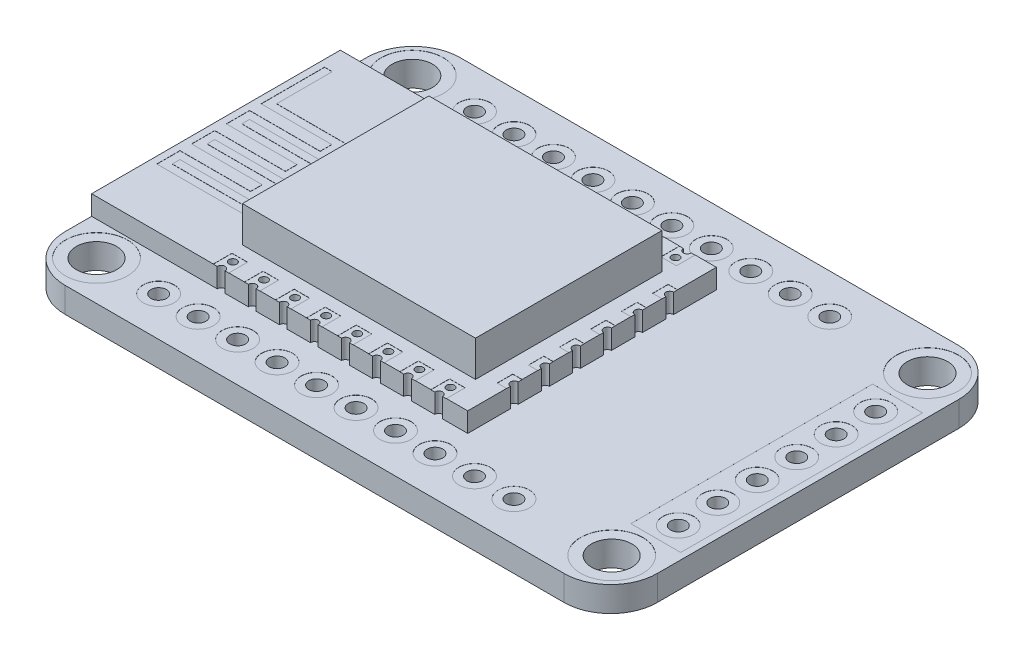
SolidWorks part; units mm, degrees
ref_plane "Front Plane" through (0, 0, 0) normal (0, 0, 1) x (1, 0, 0)
ref_plane "Top Plane" through (0, 0, 0) normal (0, 1, 0) x (1, 0, 0)
ref_plane "Right Plane" through (0, 0, 0) normal (1, 0, 0) x (0, 0, -1)
sketch "Sketch1" plane through (0, 0, 0) normal (0, 1, 0) x (1, 0, 0)
  line L1 (-19.05, -12.7) -> (19.05, -12.7)
  line L2 (-19.05, -12.7) -> (-19.05, 12.7)
  line L3 (-19.05, 12.7) -> (19.05, 12.7)
  line L4 (19.05, -12.7) -> (19.05, 12.7)
  line L5 (-19.05, -12.7) -> (19.05, 12.7) construction
  line L6 (-19.05, 12.7) -> (19.05, -12.7) construction
  point P0 (0, 0)
  dimension "D1" = 25.4
  dimension "D2" = 38.1
extrude "Boss-Extrude1" add sketch "Sketch1" along normal blind 1.62
fillet "Fillet1" radius 3 4 edges at (-19.05, 0.81, -12.7) (19.05, 0.81, -12.7) (19.05, 0.81, 12.7) (-19.05, 0.81, 12.7)
sketch "Sketch2" plane through (0, 1.62, 0) normal (0, 1, 0) x (1, 0, 0)
  line L0 (-20.6005, 0) -> (20.6768, 0) construction
  line L1 (0, 14.1473) -> (0, -15.4074) construction
  circle A0 centre (-16.575, 10.16) radius 1.3
  circle A1 centre (16.575, 10.16) radius 1.3
  circle A2 centre (16.575, -10.16) radius 1.3
  circle A3 centre (-16.575, -10.16) radius 1.3
  dimension "D1" = 2.6
  dimension "D2" = 10.16
  dimension "D3" = 16.575
extrude "Cut-Extrude1" cut sketch "Sketch2" against normal through all
sketch "Sketch4" plane through (0, 1.62, 0) normal (0, 1, 0) x (1, 0, 0)
  line L0 (-20.7466, 0) -> (20.5407, 0) construction
  line L1 (0, 13.8309) -> (0, -14.5222) construction
  circle A0 centre (16.575, 10.16) radius 2
  circle A1 centre (-16.575, 10.16) radius 2
  circle A2 centre (16.575, -10.16) radius 2
  circle A3 centre (-16.575, -10.16) radius 2
  dimension "D1" = 4
extrude "Cut-Extrude2" cut sketch "Sketch4" against normal blind 0.01
sketch "Sketch3" plane through (0, 1.62, 0) normal (0, 1, 0) x (1, 0, 0)
  line L0 (-21.1351, 0) -> (21.8987, 0) construction
  line L1 (16.575, 10.16) -> (-16.575, 10.16) construction
  line L2 (19.05, -9.7) -> (19.05, 9.7) construction
  line L3 (17.05, 6.35) -> (17.05, -6.35) construction
  circle A0 centre (-12.575, 10.16) radius 0.5
  circle A1 centre (-10.035, 10.16) radius 0.5
  circle A2 centre (-7.495, 10.16) radius 0.5
  circle A3 centre (-4.955, 10.16) radius 0.5
  circle A4 centre (-2.415, 10.16) radius 0.5
  circle A5 centre (0.125, 10.16) radius 0.5
  circle A6 centre (2.665, 10.16) radius 0.5
  circle A7 centre (5.205, 10.16) radius 0.5
  circle A8 centre (7.745, 10.16) radius 0.5
  circle A9 centre (10.285, 10.16) radius 0.5
  circle A10 centre (-16.575, 10.16) radius 1.3 construction
  circle A13 centre (10.285, -10.16) radius 0.5
  circle A14 centre (7.745, -10.16) radius 0.5
  circle A15 centre (5.205, -10.16) radius 0.5
  circle A16 centre (2.665, -10.16) radius 0.5
  circle A17 centre (0.125, -10.16) radius 0.5
  circle A18 centre (-2.415, -10.16) radius 0.5
  circle A19 centre (-4.955, -10.16) radius 0.5
  circle A20 centre (-7.495, -10.16) radius 0.5
  circle A21 centre (-10.035, -10.16) radius 0.5
  circle A22 centre (-12.575, -10.16) radius 0.5
  circle A23 centre (17.05, 6.35) radius 0.5
  circle A24 centre (17.05, 3.81) radius 0.5
  circle A25 centre (17.05, 1.27) radius 0.5
  circle A26 centre (17.05, -1.27) radius 0.5
  circle A27 centre (17.05, -3.81) radius 0.5
  circle A28 centre (17.05, -6.35) radius 0.5
  point P53 (17.05, 0)
  dimension "D1" = 1
  dimension "D5" = 2
  dimension "D3" = 2.54
  dimension "D4" = 4
  dimension "D7" = 2.54
  dimension "D2" = 10
  dimension "D6" = 6
extrude "Cut-Extrude3" cut sketch "Sketch3" against normal through all
sketch "Sketch6" plane through (0, 1.62, 0) normal (0, 1, 0) x (1, 0, 0)
  circle A0 centre (2.665, 10.16) radius 1
  circle A1 centre (2.665, 10.16) radius 0.5
  circle A2 centre (2.665, 10.16) radius 0.5 construction
  circle A3 centre (0.125, 10.16) radius 0.5
  circle A4 centre (0.125, 10.16) radius 0.5 construction
  circle A5 centre (-2.415, 10.16) radius 0.5
  circle A6 centre (-2.415, 10.16) radius 0.5 construction
  circle A7 centre (-4.955, 10.16) radius 0.5
  circle A8 centre (-4.955, 10.16) radius 0.5 construction
  circle A9 centre (-7.495, 10.16) radius 0.5
  circle A10 centre (-7.495, 10.16) radius 0.5 construction
  circle A11 centre (-10.035, 10.16) radius 0.5
  circle A12 centre (-10.035, 10.16) radius 0.5 construction
  circle A13 centre (-12.575, 10.16) radius 0.5
  circle A14 centre (-12.575, 10.16) radius 0.5 construction
  circle A15 centre (5.205, -10.16) radius 0.5
  circle A16 centre (5.205, -10.16) radius 0.5 construction
  circle A17 centre (7.745, -10.16) radius 0.5
  circle A18 centre (7.745, -10.16) radius 0.5 construction
  circle A19 centre (10.285, -10.16) radius 0.5
  circle A20 centre (10.285, -10.16) radius 0.5 construction
  circle A21 centre (10.285, 10.16) radius 0.5
  circle A22 centre (10.285, 10.16) radius 0.5 construction
  circle A23 centre (7.745, 10.16) radius 0.5
  circle A24 centre (7.745, 10.16) radius 0.5 construction
  circle A25 centre (5.205, 10.16) radius 0.5
  circle A26 centre (5.205, 10.16) radius 0.5 construction
  circle A27 centre (-12.575, -10.16) radius 0.5
  circle A28 centre (-12.575, -10.16) radius 0.5 construction
  circle A29 centre (-10.035, -10.16) radius 0.5
  circle A30 centre (-10.035, -10.16) radius 0.5 construction
  circle A31 centre (-7.495, -10.16) radius 0.5
  circle A32 centre (-7.495, -10.16) radius 0.5 construction
  circle A33 centre (-4.955, -10.16) radius 0.5
  circle A34 centre (-4.955, -10.16) radius 0.5 construction
  circle A35 centre (-2.415, -10.16) radius 0.5
  circle A36 centre (-2.415, -10.16) radius 0.5 construction
  circle A37 centre (0.125, -10.16) radius 0.5
  circle A38 centre (0.125, -10.16) radius 0.5 construction
  circle A39 centre (2.665, -10.16) radius 0.5
  circle A40 centre (2.665, -10.16) radius 0.5 construction
  circle A41 centre (17.05, -3.81) radius 0.5
  circle A42 centre (17.05, -3.81) radius 0.5 construction
  circle A43 centre (17.05, -1.27) radius 0.5
  circle A44 centre (17.05, -1.27) radius 0.5 construction
  circle A45 centre (17.05, 1.27) radius 0.5
  circle A46 centre (17.05, 1.27) radius 0.5 construction
  circle A47 centre (17.05, 3.81) radius 0.5
  circle A48 centre (17.05, 3.81) radius 0.5 construction
  circle A49 centre (17.05, 6.35) radius 0.5
  circle A50 centre (17.05, 6.35) radius 0.5 construction
  circle A51 centre (17.05, -6.35) radius 0.5
  circle A52 centre (17.05, -6.35) radius 0.5 construction
  circle A53 centre (0.125, 10.16) radius 1
  circle A54 centre (-2.415, 10.16) radius 1
  circle A55 centre (-4.955, 10.16) radius 1
  circle A56 centre (-7.495, 10.16) radius 1
  circle A57 centre (-10.035, 10.16) radius 1
  circle A58 centre (-12.575, 10.16) radius 1
  circle A59 centre (5.205, -10.16) radius 1
  circle A60 centre (7.745, -10.16) radius 1
  circle A61 centre (10.285, -10.16) radius 1
  circle A62 centre (10.285, 10.16) radius 1
  circle A63 centre (7.745, 10.16) radius 1
  circle A64 centre (5.205, 10.16) radius 1
  circle A65 centre (-12.575, -10.16) radius 1
  circle A66 centre (-10.035, -10.16) radius 1
  circle A67 centre (-7.495, -10.16) radius 1
  circle A68 centre (-4.955, -10.16) radius 1
  circle A69 centre (-2.415, -10.16) radius 1
  circle A70 centre (0.125, -10.16) radius 1
  circle A71 centre (2.665, -10.16) radius 1
  circle A72 centre (17.05, -3.81) radius 1
  circle A73 centre (17.05, -1.27) radius 1
  circle A74 centre (17.05, 1.27) radius 1
  circle A75 centre (17.05, 3.81) radius 1
  circle A76 centre (17.05, 6.35) radius 1
  circle A77 centre (17.05, -6.35) radius 1
  dimension "D1" = 0
  dimension "D2" = 0
  dimension "D3" = 0
  dimension "D4" = 0
  dimension "D5" = 0
  dimension "D6" = 0
  dimension "D7" = 0
  dimension "D8" = 0
  dimension "D9" = 0
  dimension "D10" = 0
  dimension "D11" = 0
  dimension "D12" = 0
  dimension "D13" = 0
  dimension "D14" = 0
  dimension "D15" = 0
  dimension "D16" = 0
  dimension "D17" = 0
  dimension "D18" = 0
  dimension "D19" = 0
  dimension "D20" = 0
  dimension "D21" = 0
  dimension "D22" = 0
  dimension "D23" = 0
  dimension "D24" = 0
  dimension "D25" = 0
  dimension "D26" = 0
  dimension "D27" = 0.5
extrude "Cut-Extrude4" cut sketch "Sketch6" against normal blind 0.01
sketch "Sketch7" plane through (0, 1.62, 0) normal (0, 1, 0) x (1, 0, 0)
  line L0 (-19.05, 9.7) -> (-19.05, -9.7) construction
  line L1 (-19.05, 8) -> (5.15, 8)
  line L2 (-19.05, 8) -> (-19.05, -8)
  line L3 (-19.05, -8) -> (5.15, -8)
  line L4 (5.15, 8) -> (5.15, -8)
  point P6 (-19.05, 0)
  dimension "D1" = 16
  dimension "D2" = 24.2
extrude "Boss-Extrude2" add sketch "Sketch7" along normal blind 1.26
sketch "Sketch8" plane through (0, 2.88, 0) normal (0, 1, 0) x (1, 0, 0)
  line L0 (-19.05, 8) -> (-19.05, -8) construction
  line L1 (-11.35, 6) -> (3.65, 6)
  line L2 (-11.35, 6) -> (-11.35, -6)
  line L3 (-11.35, -6) -> (3.65, -6)
  line L4 (3.65, 6) -> (3.65, -6)
  point P4 (-11.35, 0)
  dimension "D1" = 15
  dimension "D2" = 12
  dimension "D3" = 7.7
extrude "Boss-Extrude3" add sketch "Sketch8" along normal blind 2.3
sketch "Sketch9" plane through (0, 2.88, 0) normal (0, 1, 0) x (1, 0, 0)
  line L0 (-21.5126, 0) -> (22.1016, 0) construction
  line L1 (-19.05, 8) -> (-19.05, -8) construction
  line L2 (5.15, 8) -> (-19.05, 8) construction
  line L3 (5.15, -8) -> (5.15, 8) construction
  line L4 (5.15, 5) -> (5.15, -5) construction
  circle A0 centre (-10.7186, 7.2412) radius 0.25
  circle A1 centre (-8.7186, 7.2412) radius 0.25
  circle A2 centre (-6.7186, 7.2412) radius 0.25
  circle A3 centre (-4.7186, 7.2412) radius 0.25
  circle A4 centre (-2.7186, 7.2412) radius 0.25
  circle A5 centre (-0.7186, 7.2412) radius 0.25
  circle A6 centre (1.2814, 7.2412) radius 0.25
  circle A7 centre (3.2814, 7.2412) radius 0.25
  circle A8 centre (-8.7186, 7.9912) radius 0.25
  circle A9 centre (-6.7186, 7.9912) radius 0.25
  circle A10 centre (-4.7186, 7.9912) radius 0.25
  circle A11 centre (-2.7186, 7.9912) radius 0.25
  circle A12 centre (-0.7186, 7.9912) radius 0.25
  circle A13 centre (1.2814, 7.9912) radius 0.25
  circle A14 centre (3.2814, 7.9912) radius 0.25
  circle A15 centre (-10.7186, 7.9912) radius 0.25
  circle A16 centre (-10.7186, -7.9912) radius 0.25
  circle A17 centre (3.2814, -7.9912) radius 0.25
  circle A18 centre (1.2814, -7.9912) radius 0.25
  circle A19 centre (-0.7186, -7.9912) radius 0.25
  circle A20 centre (-2.7186, -7.9912) radius 0.25
  circle A21 centre (-4.7186, -7.9912) radius 0.25
  circle A22 centre (-6.7186, -7.9912) radius 0.25
  circle A23 centre (-8.7186, -7.9912) radius 0.25
  circle A24 centre (3.2814, -7.2412) radius 0.25
  circle A25 centre (1.2814, -7.2412) radius 0.25
  circle A26 centre (-0.7186, -7.2412) radius 0.25
  circle A27 centre (-2.7186, -7.2412) radius 0.25
  circle A28 centre (-4.7186, -7.2412) radius 0.25
  circle A29 centre (-6.7186, -7.2412) radius 0.25
  circle A30 centre (-8.7186, -7.2412) radius 0.25
  circle A31 centre (-10.7186, -7.2412) radius 0.25
  circle A32 centre (5.15, 5) radius 0.25
  circle A33 centre (5.15, 3) radius 0.25
  circle A34 centre (5.15, 1) radius 0.25
  circle A35 centre (5.15, -1) radius 0.25
  circle A36 centre (5.15, -3) radius 0.25
  circle A37 centre (5.15, -5) radius 0.25
  point P75 (5.15, 0)
  dimension "D1" = 0.5
  dimension "D8" = 0.5
  dimension "D4" = 0.75
  dimension "D5" = 2
  dimension "D6" = 8.3314
  dimension "D7" = 0.7588
  dimension "D10" = 2
  dimension "D2" = 8
  dimension "D3" = 2
  dimension "D9" = 6
extrude "Cut-Extrude5" cut sketch "Sketch9" against normal up to surface (1.26 mm away) up to face at (16.575, 1.62, -8.16)
sketch "Sketch10" plane through (0, 2.88, 0) normal (0, 1, 0) x (1, 0, 0)
  line L0 (-10.9685, 8) -> (-19.05, 8) construction
  line L1 (-11.2186, 8) -> (-10.2186, 8)
  line L2 (-11.2186, 8) -> (-11.2186, 6.8)
  line L3 (-11.2186, 6.8) -> (-10.2186, 6.8)
  line L4 (-10.2186, 8) -> (-10.2186, 6.8)
  line L5 (-19.6707, 0) -> (20.0452, 0) construction
  line L6 (-9.2186, 8) -> (-8.2186, 8)
  line L7 (-9.2186, 8) -> (-9.2186, 6.8)
  line L8 (-9.2186, 6.8) -> (-8.2186, 6.8)
  line L9 (-8.2186, 8) -> (-8.2186, 6.8)
  line L10 (-7.2186, 8) -> (-6.2186, 8)
  line L11 (-7.2186, 8) -> (-7.2186, 6.8)
  line L12 (-7.2186, 6.8) -> (-6.2186, 6.8)
  line L13 (-6.2186, 8) -> (-6.2186, 6.8)
  line L14 (-5.2186, 8) -> (-4.2186, 8)
  line L15 (-5.2186, 8) -> (-5.2186, 6.8)
  line L16 (-5.2186, 6.8) -> (-4.2186, 6.8)
  line L17 (-4.2186, 8) -> (-4.2186, 6.8)
  line L18 (-3.2186, 8) -> (-2.2186, 8)
  line L19 (-3.2186, 8) -> (-3.2186, 6.8)
  line L20 (-3.2186, 6.8) -> (-2.2186, 6.8)
  line L21 (-2.2186, 8) -> (-2.2186, 6.8)
  line L22 (-1.2186, 8) -> (-0.2186, 8)
  line L23 (-1.2186, 8) -> (-1.2186, 6.8)
  line L24 (-1.2186, 6.8) -> (-0.2186, 6.8)
  line L25 (-0.2186, 8) -> (-0.2186, 6.8)
  line L26 (0.7814, 8) -> (1.7814, 8)
  line L27 (0.7814, 8) -> (0.7814, 6.8)
  line L28 (0.7814, 6.8) -> (1.7814, 6.8)
  line L29 (1.7814, 8) -> (1.7814, 6.8)
  line L30 (2.7814, 8) -> (3.7814, 8)
  line L31 (2.7814, 8) -> (2.7814, 6.8)
  line L32 (2.7814, 6.8) -> (3.7814, 6.8)
  line L33 (3.7814, 8) -> (3.7814, 6.8)
  line L34 (3.7814, -8) -> (3.7814, -6.8)
  line L35 (2.7814, -6.8) -> (3.7814, -6.8)
  line L36 (2.7814, -8) -> (2.7814, -6.8)
  line L37 (2.7814, -8) -> (3.7814, -8)
  line L38 (1.7814, -8) -> (1.7814, -6.8)
  line L39 (0.7814, -6.8) -> (1.7814, -6.8)
  line L40 (0.7814, -8) -> (0.7814, -6.8)
  line L41 (0.7814, -8) -> (1.7814, -8)
  line L42 (-0.2186, -8) -> (-0.2186, -6.8)
  line L43 (-1.2186, -6.8) -> (-0.2186, -6.8)
  line L44 (-1.2186, -8) -> (-1.2186, -6.8)
  line L45 (-1.2186, -8) -> (-0.2186, -8)
  line L46 (-2.2186, -8) -> (-2.2186, -6.8)
  line L47 (-3.2186, -6.8) -> (-2.2186, -6.8)
  line L48 (-3.2186, -8) -> (-3.2186, -6.8)
  line L49 (-3.2186, -8) -> (-2.2186, -8)
  line L50 (-4.2186, -8) -> (-4.2186, -6.8)
  line L51 (-5.2186, -6.8) -> (-4.2186, -6.8)
  line L52 (-5.2186, -8) -> (-5.2186, -6.8)
  line L53 (-5.2186, -8) -> (-4.2186, -8)
  line L54 (-6.2186, -8) -> (-6.2186, -6.8)
  line L55 (-7.2186, -6.8) -> (-6.2186, -6.8)
  line L56 (-7.2186, -8) -> (-7.2186, -6.8)
  line L57 (-7.2186, -8) -> (-6.2186, -8)
  line L58 (-8.2186, -8) -> (-8.2186, -6.8)
  line L59 (-9.2186, -6.8) -> (-8.2186, -6.8)
  line L60 (-9.2186, -8) -> (-9.2186, -6.8)
  line L61 (-9.2186, -8) -> (-8.2186, -8)
  line L62 (-10.2186, -8) -> (-10.2186, -6.8)
  line L63 (-11.2186, -6.8) -> (-10.2186, -6.8)
  line L64 (-11.2186, -8) -> (-11.2186, -6.8)
  line L65 (-11.2186, -8) -> (-10.2186, -8)
  line L66 (5.15, 5.25) -> (5.15, 8) construction
  line L67 (5.15, 5.5) -> (4.55, 5.5)
  line L68 (5.15, 5.5) -> (5.15, 4.5)
  line L69 (5.15, 4.5) -> (4.55, 4.5)
  line L70 (4.55, 5.5) -> (4.55, 4.5)
  line L71 (5.15, 3.5) -> (4.55, 3.5)
  line L72 (5.15, 3.5) -> (5.15, 2.5)
  line L73 (5.15, 2.5) -> (4.55, 2.5)
  line L74 (4.55, 3.5) -> (4.55, 2.5)
  line L75 (5.15, 1.5) -> (4.55, 1.5)
  line L76 (5.15, 1.5) -> (5.15, 0.5)
  line L77 (5.15, 0.5) -> (4.55, 0.5)
  line L78 (4.55, 1.5) -> (4.55, 0.5)
  line L79 (5.15, -0.5) -> (4.55, -0.5)
  line L80 (5.15, -0.5) -> (5.15, -1.5)
  line L81 (5.15, -1.5) -> (4.55, -1.5)
  line L82 (4.55, -0.5) -> (4.55, -1.5)
  line L83 (5.15, -2.5) -> (4.55, -2.5)
  line L84 (5.15, -2.5) -> (5.15, -3.5)
  line L85 (5.15, -3.5) -> (4.55, -3.5)
  line L86 (4.55, -2.5) -> (4.55, -3.5)
  line L87 (5.15, -4.5) -> (4.55, -4.5)
  line L88 (5.15, -4.5) -> (5.15, -5.5)
  line L89 (5.15, -5.5) -> (4.55, -5.5)
  line L90 (4.55, -4.5) -> (4.55, -5.5)
  line L91 (-18.6082, 6.5485) -> (-18.6082, 2.4658)
  line L92 (-18.6082, 2.4658) -> (-14.065, 2.4658)
  line L93 (-14.065, 2.4658) -> (-14.065, 1.7212)
  line L94 (-14.065, 1.7212) -> (-18.6082, 1.7212)
  line L95 (-18.6082, 1.7212) -> (-18.6082, 0.2282)
  line L96 (-18.6082, 0.2282) -> (-14.065, 0.2282)
  line L97 (-14.065, 0.2282) -> (-14.065, -0.5165)
  line L98 (-14.065, -0.5165) -> (-18.6082, -0.5165)
  line L99 (-18.6082, -0.5165) -> (-18.6082, -2.0095)
  line L100 (-18.6082, -2.0095) -> (-14.065, -2.0095)
  line L101 (-14.065, -2.0095) -> (-14.065, -2.7541)
  line L102 (-14.065, -2.7541) -> (-18.6082, -2.7541)
  line L103 (-18.6082, -2.7541) -> (-18.6082, -4.2472)
  line L104 (-18.6082, -4.2472) -> (-11.8485, -4.2472)
  line L105 (-11.8485, -4.2472) -> (-11.8485, 2.4658)
  line L106 (-18.1082, 6.5485) -> (-18.1082, 2.9658)
  line L107 (-18.1082, 2.9658) -> (-13.565, 2.9658)
  line L108 (-13.565, 2.9658) -> (-13.565, 1.2212)
  line L109 (-13.565, 1.2212) -> (-18.1082, 1.2212)
  line L110 (-18.1082, 1.2212) -> (-18.1082, 0.7282)
  line L111 (-18.1082, 0.7282) -> (-13.565, 0.7282)
  line L112 (-13.565, 0.7282) -> (-13.565, -1.0165)
  line L113 (-13.565, -1.0165) -> (-18.1082, -1.0165)
  line L114 (-18.1082, -1.0165) -> (-18.1082, -1.5095)
  line L115 (-18.1082, -1.5095) -> (-13.565, -1.5095)
  line L116 (-13.565, -1.5095) -> (-13.565, -3.2541)
  line L117 (-13.565, -3.2541) -> (-18.1082, -3.2541)
  line L118 (-18.1082, -3.2541) -> (-18.1082, -3.7472)
  line L119 (-18.1082, -3.7472) -> (-12.3485, -3.7472)
  line L120 (-12.3485, -3.7472) -> (-12.3485, 2.4658)
  line L121 (-18.1082, 6.5485) -> (-18.6082, 6.5485)
  line L122 (-11.8485, 2.4658) -> (-12.3485, 2.4658)
  point P6 (-10.7186, 7.2412)
  point P8 (-10.7186, 6.8)
  point P17 (-8.7186, 7.2412)
  point P22 (-6.7186, 7.2412)
  point P27 (-4.7186, 7.2412)
  point P32 (-2.7186, 7.2412)
  point P37 (-0.7186, 7.2412)
  point P42 (1.2814, 7.2412)
  point P47 (3.2814, 7.2412)
  point P79 (3.2814, -7.2412)
  point P80 (1.2814, -7.2412)
  point P81 (-0.7186, -7.2412)
  point P82 (-2.7186, -7.2412)
  point P83 (-4.7186, -7.2412)
  point P84 (-6.7186, -7.2412)
  point P85 (-8.7186, -7.2412)
  point P86 (-10.7186, -7.2412)
  point P93 (5.15, 5)
  point P94 (4.55, 5)
  point P102 (5.15, 3)
  point P107 (5.15, 1)
  point P112 (5.15, -1)
  point P117 (5.15, -3)
  point P122 (5.15, -5)
  dimension "D1" = 1
  dimension "D2" = 1.2
  dimension "D4" = 1
  dimension "D5" = 0.6
  dimension "D7" = 0.5
  dimension "D3" = 8
  dimension "D6" = 6
extrude "Cut-Extrude6" cut sketch "Sketch10" against normal blind 0.01
sketch "Sketch11" plane through (0, 1.62, 0) normal (0, 1, 0) x (1, 0, 0)
  line L1 (15.4246, 7.7792) -> (18.6356, 7.7792)
  line L2 (15.4246, 7.7792) -> (15.4246, -7.7792)
  line L3 (15.4246, -7.7792) -> (18.6356, -7.7792)
  line L4 (18.6356, 7.7792) -> (18.6356, -7.7792)
  point P4 (18.6356, 0)
extrude "Cut-Extrude8" cut sketch "Sketch11" against normal blind 0.001
